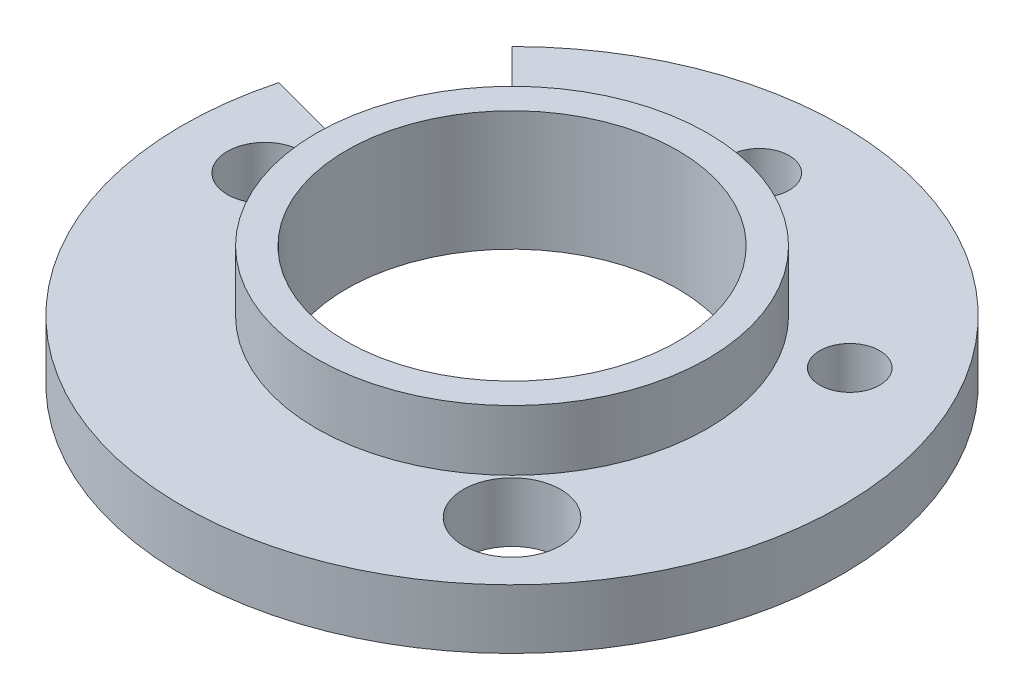
SolidWorks part; units mm, degrees
material "Brass"
ref_plane "Front Plane" through (0, 0, 0) normal (0, 0, 1) x (1, 0, 0)
ref_plane "Top Plane" through (0, 0, 0) normal (0, 1, 0) x (1, 0, 0)
ref_plane "Right Plane" through (0, 0, 0) normal (1, 0, 0) x (0, 0, -1)
sketch "Sketch1" plane through (0, 0, 0) normal (0, 0, 1) x (1, 0, 0)
  line L0 (0, 0) -> (0, 50.189) construction
  line L1 (11.05, 0) -> (11.05, 50.189) construction
  line L2 (11.05, 0) -> (11.05, 8)
  line L3 (11.05, 8) -> (13.05, 8)
  line L4 (13.05, 8) -> (13.05, 3.9693)
  line L5 (13.05, 3.9693) -> (22, 3.9693)
  line L6 (22, 3.9693) -> (22, 0)
  line L7 (22, 0) -> (11.05, 0)
  dimension "D1" = 11.05
  dimension "D2" = 8
  dimension "D3" = 22
revolve "Revolve1" add sketch "Sketch1" angle 360 about L0
sketch "Sketch3" plane through (0, 0, 0) normal (0, 1, 0) x (1, 0, 0)
  line L0 (0, 0) -> (29.292, 0) construction
  line L1 (0, 0) -> (-28.8006, 0) construction
  line L2 (-12.6624, 3.3929) -> (0, 0) construction
  line L3 (0, 0) -> (-16.2001, 16.2001) construction
  line L4 (-16.442, 16.442) -> (-9.2696, 9.2696)
  line L5 (-22.4603, 6.0182) -> (-12.6624, 3.3929)
  circle A0 centre (0, 0) radius 16.5 construction
  circle A4 centre (-16.5, 0) radius 2.5
  arc A5 (-9.2696, 9.2696) -> (-12.6624, 3.3929) centre (0, 0) ccw
  arc A6 (16.5, 0) -> (11.6673, -11.6673) centre (0, 0) cw construction
  circle A7 centre (11.6673, -11.6673) radius 3.25
  arc A8 (14.2894, 8.25) -> (16.5, 0) centre (0, 0) cw construction
  circle A9 centre (14.2894, 8.25) radius 2
  circle A10 centre (16.5, 0) radius 3.005 construction
  circle A11 centre (0, 16.5) radius 2
  arc A12 (-16.442, 16.442) -> (-22.4603, 6.0182) centre (0, 0) ccw
  point P12 (0, 0)
  point P20 (-14, 0)
  point P22 (-19, 0)
  dimension "D3" = 30
  dimension "D2" = 135
extrude "Cut-Extrude1" cut sketch "Sketch3" along normal blind 10
equation "\"OPENING\"= 30deg"
equation "\"D2@Sketch3\"=\"OFFSET\""
equation "\"OFFSET\"= 135deg"
